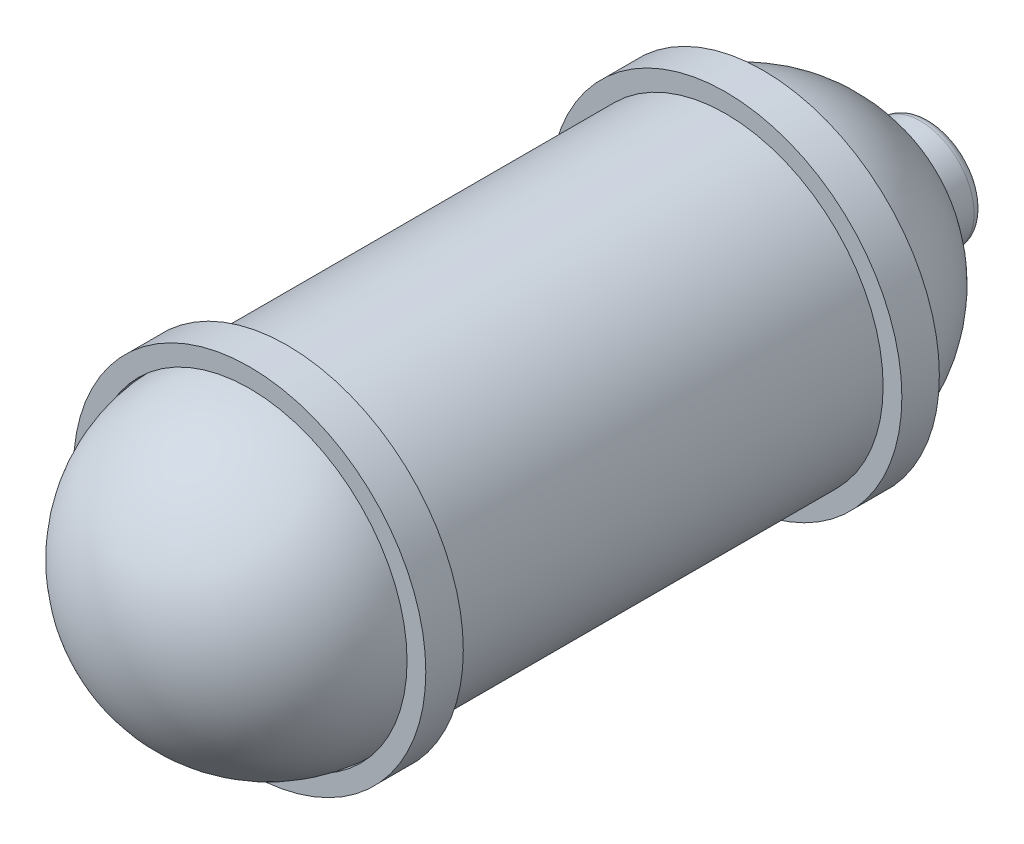
SolidWorks part; units mm, degrees
material "Ti-6Al-4VSolution treated and aged (SS)"
ref_plane "Front Plane" through (0, 0, 0) normal (0, 0, 1) x (1, 0, 0)
ref_plane "Top Plane" through (0, 0, 0) normal (0, 1, 0) x (1, 0, 0)
ref_plane "Right Plane" through (0, 0, 0) normal (1, 0, 0) x (0, 0, -1)
sketch "Sketch1" plane through (0, 0, 0) normal (0, 0, 1) x (1, 0, 0)
  circle A0 centre (0, 0) radius 840
  circle A1 centre (0, 0) radius 710
  dimension "D1" = 1680
  dimension "D2" = 1420
extrude "Boss-Extrude1" add sketch "Sketch1" along normal mid plane 2540
sketch "Sketch4" plane through (0, 0, 0) normal (1, 0, 0) x (0, 0, -1)
  line L0 (1270, -840) -> (1270, 840) construction
  line L1 (1270, 840) -> (-1270, 840) construction
  line L2 (1270, 840) -> (1270, 710)
  line L3 (1980, 0) -> (2110, 0)
  line L4 (1270, 0) -> (4053.2003, 0) construction
  arc A0 (1270, 840) -> (2110, 0) centre (1270, 0) cw
  arc A1 (1270, 710) -> (1980, 0) centre (1270, 0) cw
  dimension "D1" = 710
revolve "Revolve1" add sketch "Sketch4" angle 360 about L4
mirror "Mirror1" about plane through (0, 0, 0) normal (0, 0, 1) of "Revolve1"
ref_plane "Plane1" through (0, 0, -1270) normal (0, 0, 1) x (1, 0, 0)
sketch "Sketch5" plane through (0, 0, -1270) normal (0, 0, 1) x (1, 0, 0)
  circle A0 centre (0, 0) radius 840
  circle A1 centre (0, 0) radius 940
  dimension "D1" = 1680
  dimension "D2" = 1880
extrude "Boss-Extrude2" add sketch "Sketch5" along normal mid plane 200
mirror "Mirror2" about plane through (0, 0, 0) normal (0, 0, 1) of "Boss-Extrude2"
ref_plane "Plane2" through (0, 0, -2110) normal (0, 0, -1) x (-1, 0, 0)
sketch "Sketch7" plane through (0, 0, -2110) normal (0, 0, -1) x (-1, 0, 0)
  circle A0 centre (0, 0) radius 400
  dimension "D1" = 800
extrude "Cut-Extrude1" cut sketch "Sketch7" against normal mid plane 100
ref_plane "Plane3" through (0, 0, -2060) normal (0, 0, -1) x (-1, 0, 0)
sketch "Sketch10" plane through (0, 0, -2060) normal (0, 0, -1) x (-1, 0, 0)
  circle A0 centre (0, 0) radius 285.482
  circle A1 centre (0, 0) radius 285.482 construction
extrude "Cut-Extrude2" cut sketch "Sketch10" against normal blind 340
ref_plane "Plane4" through (0, 0, -2060) normal (0, 0, 1) x (1, 0, 0)
sketch "Sketch11" plane through (0, 0, -2060) normal (0, 0, 1) x (1, 0, 0)
  circle A0 centre (0, 0) radius 285.482
  circle A1 centre (0, 0) radius 285.482 construction
extrude "Boss-Extrude4" add sketch "Sketch11" against normal blind 200 separate body
fillet "Fillet2" radius 50 1 edges at (285.482, 0, -2260)
